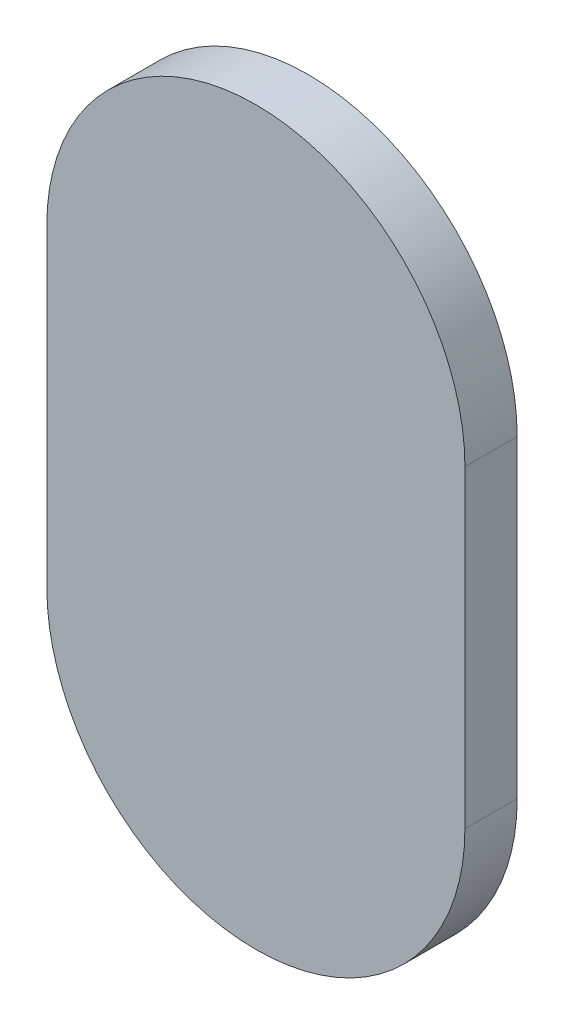
SolidWorks part; units mm, degrees
ref_plane "Ön Düzlem" through (0, 0, 0) normal (0, 0, 1) x (1, 0, 0)
ref_plane "Üst Düzlem" through (0, 0, 0) normal (0, 1, 0) x (1, 0, 0)
ref_plane "Sağ Düzlem" through (0, 0, 0) normal (1, 0, 0) x (0, 0, -1)
sketch "Sketch1" plane through (0, 0, 0) normal (0, 0, 1) x (1, 0, 0)
  line L0 (0, 0) -> (0, -3) construction
  line L1 (2, 0) -> (2, -3)
  line L2 (-2, 0) -> (-2, -3)
  arc A0 (2, 0) -> (-2, 0) centre (0, 0) ccw
  arc A1 (-2, -3) -> (2, -3) centre (0, -3) ccw
  point P3 (0, -1.5)
  dimension "D2" = 7
  dimension "D1" = 4
extrude "Boss-Extrude1" add sketch "Sketch1" along normal blind 0.5
